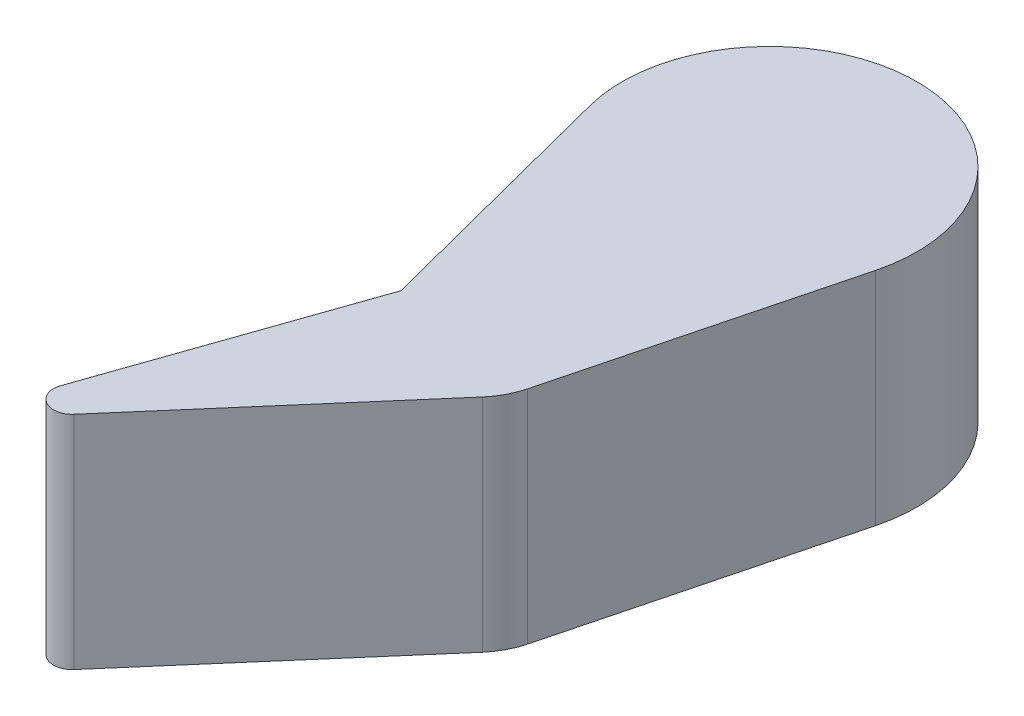
SolidWorks part; units mm, degrees
ref_plane "Front Plane" through (0, 0, 0) normal (0, 0, 1) x (1, 0, 0)
ref_plane "Top Plane" through (0, 0, 0) normal (0, 1, 0) x (1, 0, 0)
ref_plane "Right Plane" through (0, 0, 0) normal (1, 0, 0) x (0, 0, -1)
sketch "Sketch1" plane through (0, 0, 0) normal (0, 1, 0) x (1, 0, 0)
  line L4 (-38.7298, -10) -> (-20.8779, -79.1404)
  line L5 (38.7298, -10) -> (19.3649, -85)
  line L6 (15.1383, -93.0702) -> (-36.2154, -152.5496)
  line L7 (-20.8779, -79.1404) -> (-44.7221, -147.6383)
  arc A0 (38.7298, -10) -> (-38.7298, -10) centre (0, 0) ccw
  arc A2 (-44.7221, -147.6383) -> (-36.2154, -152.5496) centre (-40, -149.282) ccw
  arc A3 (15.1383, -93.0702) -> (19.3649, -85) centre (0, -80) ccw
  dimension "D1" = 80
  dimension "D5" = 10
  dimension "D2" = 80
  dimension "D3" = 80
extrude "Boss-Extrude1" add sketch "Sketch1" along normal blind 60
